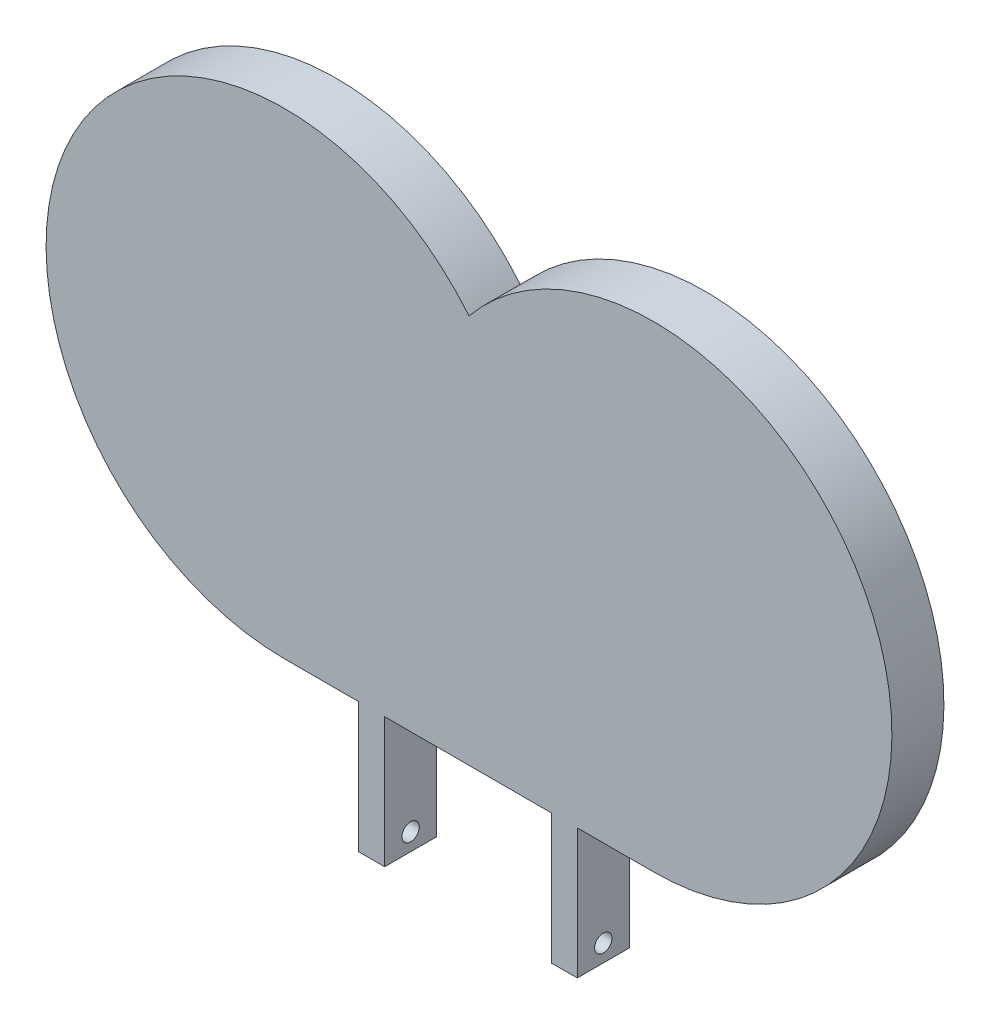
SolidWorks part; units mm, degrees
ref_plane "Ön Düzlem" through (0, 0, 0) normal (0, 0, 1) x (1, 0, 0)
ref_plane "Üst Düzlem" through (0, 0, 0) normal (0, 1, 0) x (1, 0, 0)
ref_plane "Sağ Düzlem" through (0, 0, 0) normal (1, 0, 0) x (0, 0, -1)
sketch "Çizim1" plane through (0, 0, 0) normal (0, 0, 1) x (1, 0, 0)
  line L1 (-2.8808, -55) -> (82.2973, -55)
  arc A0 (82.2973, -55) -> (39.7083, 34.8019) centre (82.2973, 0) ccw
  arc A1 (39.7083, 34.8019) -> (-2.8808, -55) centre (-2.8808, 0) ccw
extrude "Yükseklik-Ekstrüzyon1" add sketch "Çizim1" along normal blind 12
sketch "Çizim2" plane through (0, 0, 0) normal (0, 0, 1) x (1, 0, 0)
  line L0 (82.2973, -53.5) -> (-2.8808, -53.5)
  arc A0 (82.2973, -53.5) -> (39.7083, 32.3794) centre (82.2973, 0) ccw
  arc A1 (39.7083, 32.3794) -> (-2.8808, -53.5) centre (-2.8808, 0) ccw
  dimension "D1" = 107
  dimension "D2" = 107
extrude "Kes-Ekstrüzyon1" cut sketch "Çizim2" against normal mid plane 20
sketch "Çizim3" plane through (0, -55, 0) normal (0, -1, 0) x (1, 0, 0)
  line L0 (25.2955, 4.9964) -> (25.2955, 0)
  line L2 (-2.8808, 0) -> (82.2973, 0) construction
  line L3 (25.2955, 0) -> (33.431, 0)
  line L4 (33.431, 0) -> (33.431, 4.9964)
  line L5 (35.4225, 4.9964) -> (35.4225, 0)
  line L6 (35.4225, 0) -> (43.4225, 0)
  line L7 (43.4225, 0) -> (43.4225, 4.9964)
  line L8 (45.6194, 4.9964) -> (45.6194, 0)
  line L9 (45.6194, 0) -> (53.8876, 0)
  line L10 (53.8876, 0) -> (53.8876, 4.9964)
  arc A0 (43.4225, 4.9964) -> (35.4225, 4.9964) centre (39.4225, 4.9964) ccw
  arc A1 (53.8876, 4.9964) -> (45.6194, 4.9964) centre (49.7535, 4.9964) ccw
  arc A2 (33.431, 4.9964) -> (25.2955, 4.9964) centre (29.3633, 4.9964) ccw
extrude "Kes-Ekstrüzyon4" cut sketch "Çizim3" against normal blind 20
sketch "Çizim4" plane through (0, -55, 0) normal (0, -1, 0) x (-1, 0, 0)
  line L0 (2.8808, -12) -> (-82.2973, -12) construction
  line L1 (-20.2438, -12) -> (-14.2438, -12)
  line L2 (-20.2438, -12) -> (-20.2438, 0)
  line L3 (-20.2438, 0) -> (-14.2438, 0)
  line L4 (-14.2438, -12) -> (-14.2438, 0)
  line L5 (2.8808, 0) -> (-25.2955, 0) construction
  line L6 (-53.8876, 0) -> (-82.2973, 0) construction
  line L7 (-64.6954, -12) -> (-58.6954, -12)
  line L8 (-64.6954, -12) -> (-64.6954, 0)
  line L9 (-64.6954, 0) -> (-58.6954, 0)
  line L10 (-58.6954, -12) -> (-58.6954, 0)
  dimension "D1" = 6
  dimension "D2" = 6
extrude "Yükseklik-Ekstrüzyon2" add sketch "Çizim4" along normal blind 30
sketch "Çizim5" plane through (64.6954, 0, 0) normal (1, 0, 0) x (0, 0, -1)
  circle A0 centre (-6, -81.0046) radius 2
  point P2 (-6, -81.0046)
  dimension "D1" = 4
extrude "Kes-Ekstrüzyon5" cut sketch "Çizim5" against normal blind 60
